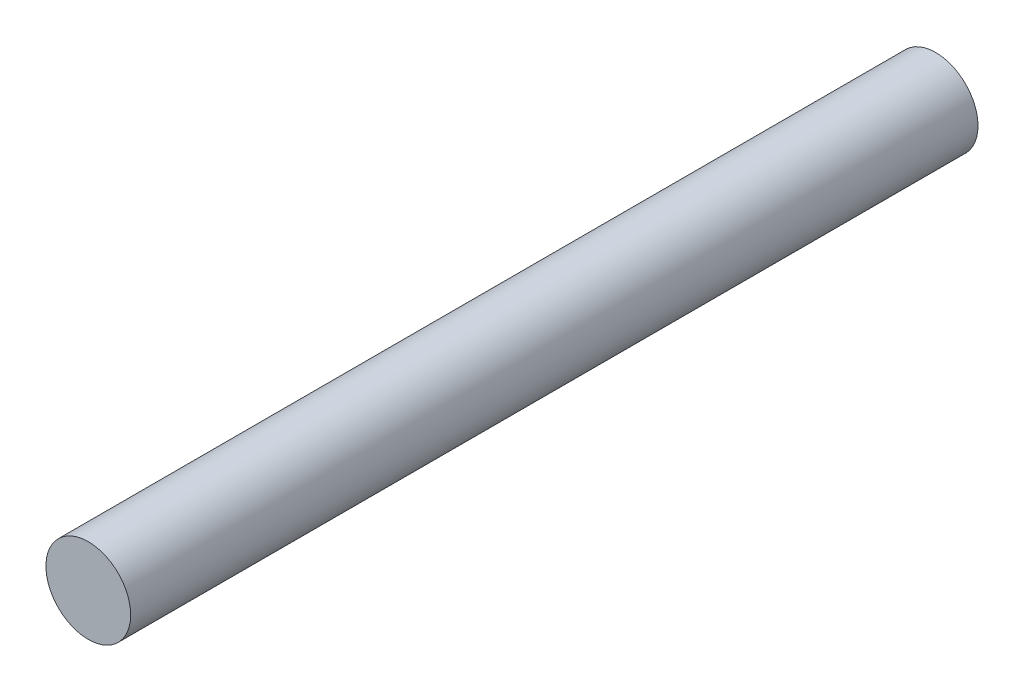
SolidWorks part; units mm, degrees
ref_plane "Front Plane" through (0, 0, 0) normal (0, 0, 1) x (1, 0, 0)
ref_plane "Top Plane" through (0, 0, 0) normal (0, 1, 0) x (1, 0, 0)
ref_plane "Right Plane" through (0, 0, 0) normal (1, 0, 0) x (0, 0, -1)
sketch "Sketch1" plane through (0, 0, 0) normal (0, 0, 1) x (1, 0, 0)
  circle A0 centre (0, 0) radius 500
  dimension "D1" = 1000
extrude "Boss-Extrude1" add sketch "Sketch1" along normal blind 10000
